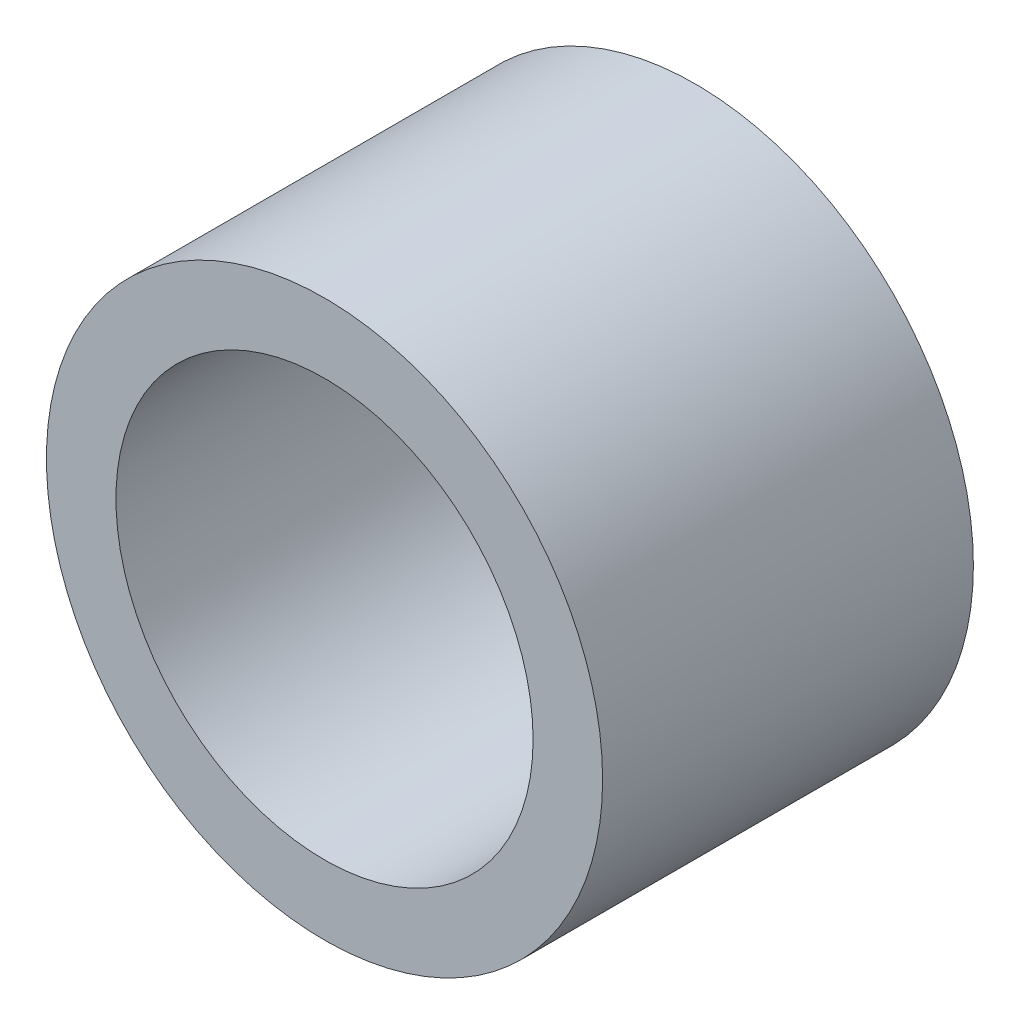
SolidWorks part; units mm, degrees
ref_plane "Plan de face" through (0, 0, 0) normal (0, 0, 1) x (1, 0, 0)
ref_plane "Plan de dessus" through (0, 0, 0) normal (0, 1, 0) x (1, 0, 0)
ref_plane "Plan de droite" through (0, 0, 0) normal (1, 0, 0) x (0, 0, -1)
sketch "Esquisse1" plane through (0, 0, 0) normal (0, 0, 1) x (1, 0, 0)
  circle A0 centre (0, 0) radius 45
  circle A1 centre (0, 0) radius 60
  dimension "D1" = 90
  dimension "D2" = 120
extrude "Boss.-Extru.1" add sketch "Esquisse1" along normal blind 80
